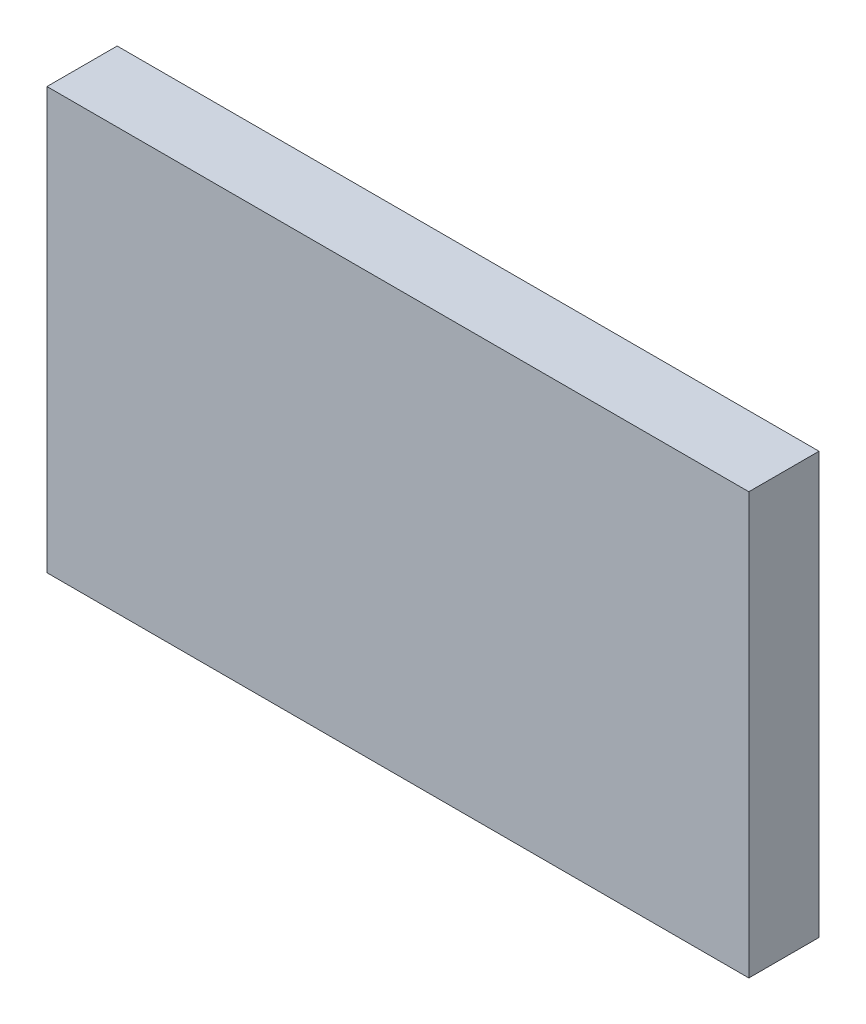
SolidWorks part; units mm, degrees
ref_plane "Front Plane" through (0, 0, 0) normal (0, 0, 1) x (1, 0, 0)
ref_plane "Top Plane" through (0, 0, 0) normal (0, 1, 0) x (1, 0, 0)
ref_plane "Right Plane" through (0, 0, 0) normal (1, 0, 0) x (0, 0, -1)
sketch "Sketch1" plane through (0, 0, 0) normal (0, 0, 1) x (1, 0, 0)
  line L0 (0, 0) -> (0, 12)
  line L1 (0, 12) -> (7.5, 12)
  line L7 (7.4971, 0) -> (0, 0)
  line L8 (7.5, 12) -> (12.5, 12)
  line L9 (10, 16.2871) -> (10, 12) construction
  line L15 (20, 12) -> (12.5, 12)
  line L16 (20, 0) -> (20, 12)
  line L17 (12.5029, 0) -> (20, 0)
  line L18 (7.5, 12) -> (12.5, 12)
  line L19 (7.4971, 0) -> (12.5029, 0)
  point P4 (10, 12)
  dimension "D1" = 12
  dimension "D2" = 7.5
  dimension "D6" = 5
extrude "Boss-Extrude1" add sketch "Sketch1" along normal blind 2 contours L7 L19 L17 L16 L15 L18 L8 L1 L0
